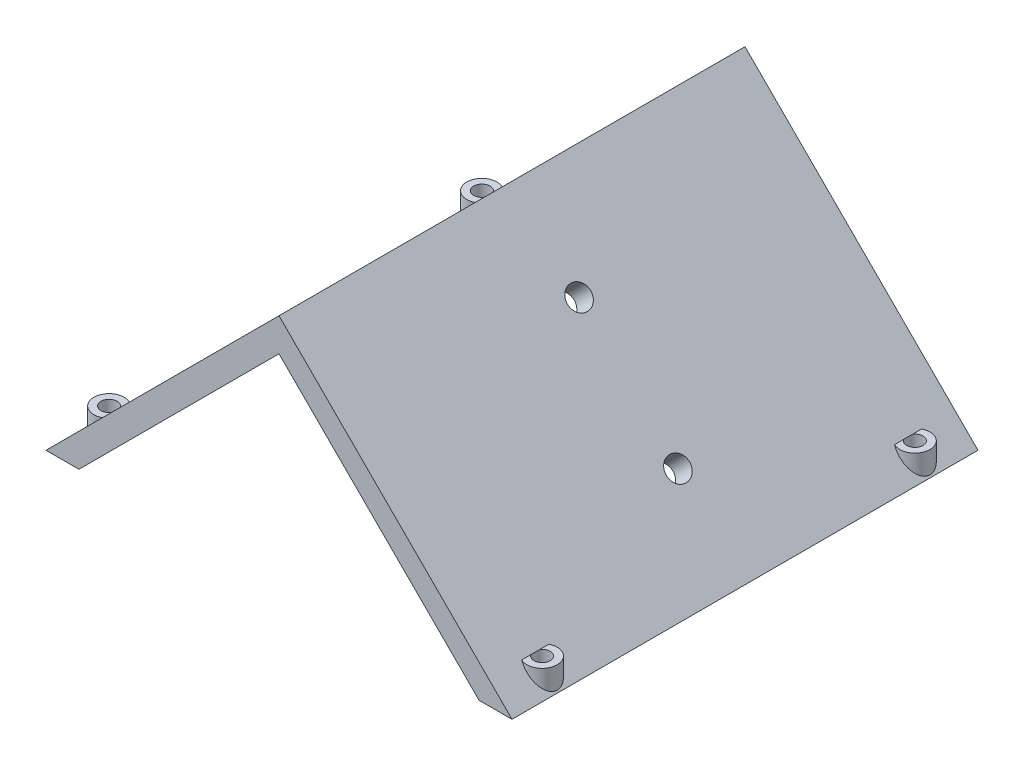
SolidWorks part; units mm, degrees
ref_plane "前视基准面" through (0, 0, 0) normal (0, 0, 1) x (1, 0, 0)
ref_plane "上视基准面" through (0, 0, 0) normal (0, 1, 0) x (1, 0, 0)
ref_plane "右视基准面" through (0, 0, 0) normal (1, 0, 0) x (0, 0, -1)
other "Configuration Table"
sketch "草图1" plane through (0, 0, 0) normal (0, 0, 1) x (1, 0, 0)
  line L0 (50, 3.55) -> (50, 51.0215) construction
  line L1 (0, 0) -> (100, 0) construction
  line L2 (0, 0) -> (0, 7.1) construction
  line L3 (0, 7.1) -> (100, 7.1) construction
  line L4 (100, 0) -> (100, 7.1) construction
  line L5 (0, 0) -> (100, 7.1) construction
  line L6 (0, 7.1) -> (100, 0) construction
  line L7 (0, 7.1) -> (50, 57.1)
  line L8 (50, 57.1) -> (100, 7.1)
  line L9 (7.0711, 7.1) -> (50, 50.0289)
  line L10 (50, 50.0289) -> (92.9289, 7.1)
  line L11 (0, 7.1) -> (7.0711, 7.1)
  line L12 (92.9289, 7.1) -> (100, 7.1)
  point P4 (50, 3.55)
  dimension "D1" = 100
  dimension "D2" = 7.1
  dimension "D3" = 5
extrude "凸台-拉伸1" add sketch "草图1" along normal blind 100
sketch "草图2" plane through (53.55, 53.55, 0) normal (0.7071, 0.7071, 0) x (0, 0, -1)
  line L0 (-100, -30.3349) -> (0, -30.3349) construction
  line L1 (-100, -65.6902) -> (-100, 5.0205) construction
  line L2 (0, -65.6902) -> (0, 5.0205) construction
  line L3 (-50, 5.0205) -> (-50, -65.0551) construction
  line L4 (-100, 5.0205) -> (0, 5.0205) construction
  line L5 (-50, -15.3349) -> (-50, -45.3349)
  circle A0 centre (-50, -15.3349) radius 2.5
  circle A1 centre (-50, -45.3349) radius 2.5
  point P14 (-50, -30.3349)
  dimension "D1" = 5
  dimension "D2" = 5
  dimension "D3" = 30
extrude "切除-拉伸1" cut sketch "草图2" against normal blind 100
sketch "草图3" plane through (0, 7.1, 0) normal (0, -1, 0) x (1, 0, 0)
  line L0 (96.4645, 100) -> (96.4645, 0) construction
  line L4 (92.9289, 0) -> (100, 0)
  line L5 (100, 0) -> (100, 100)
  line L6 (100, 100) -> (92.9289, 100)
  line L7 (92.9289, 100) -> (92.9289, 0)
  line L8 (92.9289, 0) -> (100, 0)
  line L9 (100, 0) -> (100, 100) construction
  line L10 (100, 100) -> (92.9289, 100) construction
  line L11 (92.9289, 100) -> (92.9289, 0) construction
  circle A0 centre (96.4645, 90) radius 1.75
  circle A1 centre (96.4645, 10) radius 1.75
  circle A2 centre (96.4645, 90) radius 3.25
  circle A3 centre (96.4645, 10) radius 3.25
  dimension "D2" = 3.5
  dimension "D4" = 3.5
  dimension "D3" = 10
  dimension "D5" = 10
  dimension "D1" = 0
  dimension "D6" = 1.5
extrude "凸台-拉伸2" add sketch "草图3" against normal blind 5 contours A2 A0 | A3 A1
sketch "草图4" plane through (0, 7.1, 0) normal (0, -1, 0) x (1, 0, 0)
  line L0 (92.9289, 0) -> (100, 0) construction
  line L1 (92.9289, 0) -> (100, 0)
  line L4 (92.9289, 0) -> (100, 0)
  line L5 (100, 0) -> (100, 100)
  line L6 (100, 100) -> (92.9289, 100)
  line L7 (92.9289, 100) -> (92.9289, 0)
  line L8 (92.9289, 0) -> (100, 0)
  line L9 (100, 0) -> (100, 100)
  line L10 (100, 100) -> (92.9289, 100)
  line L11 (92.9289, 100) -> (92.9289, 0)
  circle A1 centre (96.4645, 10) radius 3.25
  circle A2 centre (96.4645, 10) radius 3.25
  circle A3 centre (96.4645, 90) radius 3.25
  circle A4 centre (96.4645, 90) radius 3.25
  circle A5 centre (96.4645, 10) radius 1.75
  circle A6 centre (96.4645, 10) radius 1.75
  circle A7 centre (96.4645, 90) radius 1.75
  circle A8 centre (96.4645, 90) radius 1.75
  dimension "D1" = 0
  dimension "D2" = 0
  dimension "D3" = 0
  dimension "D4" = 0
  dimension "D5" = 0
extrude "切除-拉伸3" cut sketch "草图4" against normal blind 5 contours A8 | A6
sketch "草图5" plane through (0, 7.1, 0) normal (0, -1, 0) x (1, 0, 0)
  line L0 (92.9289, 0) -> (100, 0) construction
  line L1 (92.9289, 0) -> (100, 0)
  line L2 (50, 100) -> (50, 0) construction
  line L3 (50, 100) -> (50, 0)
  line L4 (0, 0) -> (7.0711, 0)
  line L5 (7.0711, 0) -> (7.0711, 100)
  line L6 (7.0711, 100) -> (0, 100)
  line L7 (0, 100) -> (0, 0)
  line L8 (0, 0) -> (7.0711, 0)
  line L9 (7.0711, 0) -> (7.0711, 100)
  line L10 (7.0711, 100) -> (0, 100)
  line L11 (0, 100) -> (0, 0)
  circle A0 centre (3.5355, 90) radius 1.75
  circle A1 centre (96.4645, 10) radius 3.25
  circle A2 centre (96.4645, 10) radius 3.25
  circle A3 centre (96.4645, 90) radius 3.25
  circle A4 centre (96.4645, 90) radius 3.25
  circle A5 centre (96.4645, 10) radius 1.75
  circle A6 centre (96.4645, 10) radius 1.75
  circle A7 centre (96.4645, 90) radius 1.75
  circle A8 centre (96.4645, 90) radius 1.75
  circle A9 centre (3.5355, 10) radius 1.75
  circle A10 centre (3.5355, 90) radius 3.25
  circle A11 centre (3.5355, 10) radius 3.25
  dimension "D1" = 0
  dimension "D2" = 0
  dimension "D3" = 0
  dimension "D4" = 0
  dimension "D5" = 0
extrude "凸台-拉伸3" add sketch "草图5" against normal blind 5 contours A10 A0 | A11 A9
sketch "草图6" plane through (0, 7.1, 0) normal (0, -1, 0) x (1, 0, 0)
  line L0 (92.9289, 0) -> (100, 0) construction
  line L1 (50, 100) -> (50, 0) construction
  line L2 (92.9289, 0) -> (100, 0)
  line L3 (50, 100) -> (50, 0)
  line L4 (0, 0) -> (7.0711, 0)
  line L5 (7.0711, 0) -> (7.0711, 100)
  line L6 (7.0711, 100) -> (0, 100)
  line L7 (0, 100) -> (0, 0)
  line L8 (0, 0) -> (7.0711, 0)
  line L9 (7.0711, 0) -> (7.0711, 100)
  line L10 (7.0711, 100) -> (0, 100)
  line L11 (0, 100) -> (0, 0)
  line L12 (0, 0) -> (7.0711, 0)
  line L13 (7.0711, 0) -> (7.0711, 100)
  line L14 (7.0711, 100) -> (0, 100)
  line L15 (0, 100) -> (0, 0)
  line L16 (0, 0) -> (7.0711, 0)
  line L17 (7.0711, 0) -> (7.0711, 100)
  line L18 (7.0711, 100) -> (0, 100)
  line L19 (0, 100) -> (0, 0)
  circle A1 centre (96.4645, 10) radius 1.75
  circle A2 centre (96.4645, 10) radius 1.75
  circle A3 centre (96.4645, 90) radius 3.25
  circle A4 centre (96.4645, 90) radius 3.25
  circle A5 centre (96.4645, 10) radius 3.25
  circle A6 centre (96.4645, 10) radius 3.25
  circle A7 centre (3.5355, 10) radius 3.25
  circle A8 centre (3.5355, 10) radius 3.25
  circle A9 centre (3.5355, 90) radius 3.25
  circle A10 centre (3.5355, 90) radius 3.25
  circle A11 centre (3.5355, 10) radius 1.75
  circle A12 centre (3.5355, 10) radius 1.75
  circle A13 centre (96.4645, 90) radius 1.75
  circle A14 centre (96.4645, 90) radius 1.75
  circle A15 centre (3.5355, 90) radius 1.75
  circle A16 centre (3.5355, 90) radius 1.75
  dimension "D1" = 0
  dimension "D2" = 0
  dimension "D3" = 0
  dimension "D4" = 0
  dimension "D5" = 0
  dimension "D6" = 0
  dimension "D7" = 0
  dimension "D8" = 0
  dimension "D9" = 0
  dimension "D10" = 0
extrude "切除-拉伸4" cut sketch "草图6" against normal blind 5 contours A12 | A16
